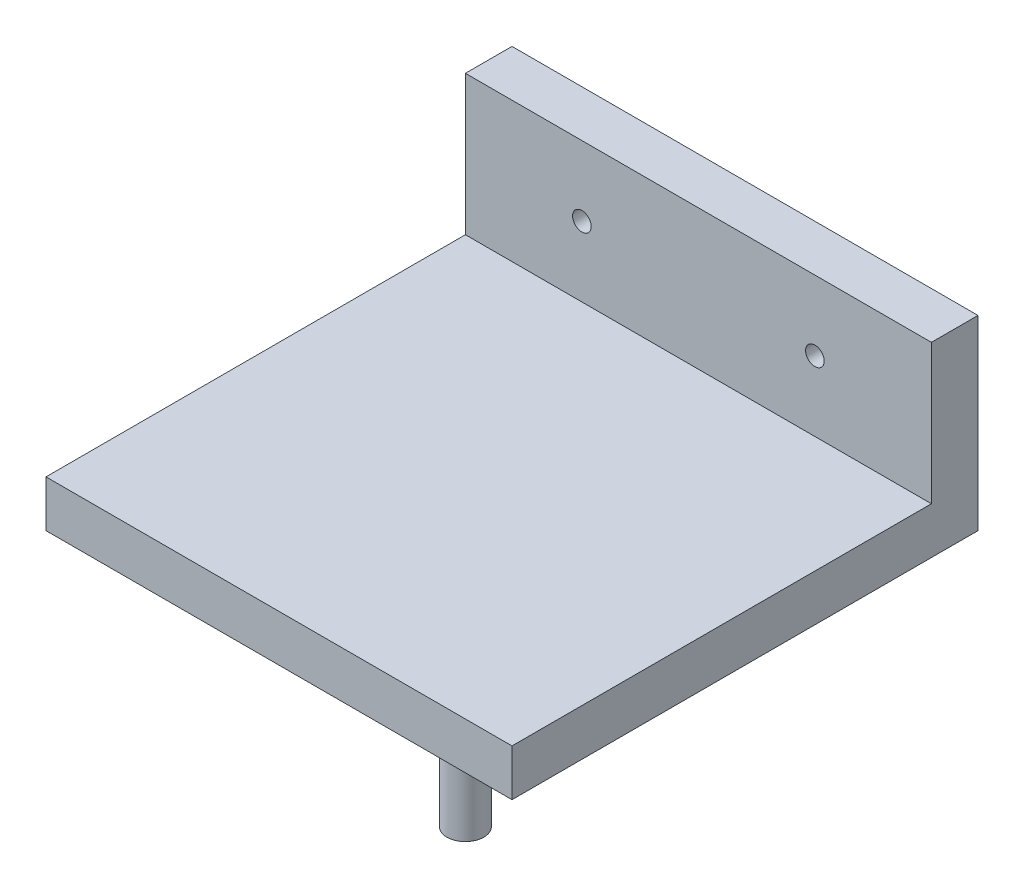
SolidWorks part; units mm, degrees
ref_plane "Front Plane" through (0, 0, 0) normal (0, 0, 1) x (1, 0, 0)
ref_plane "Top Plane" through (0, 0, 0) normal (0, 1, 0) x (1, 0, 0)
ref_plane "Right Plane" through (0, 0, 0) normal (1, 0, 0) x (0, 0, -1)
sketch "Sketch1" plane through (0, 0, 0) normal (0, 0, 1) x (1, 0, 0)
  line L1 (-50, 20) -> (50, 20)
  line L2 (-50, 20) -> (-50, -20)
  line L3 (-50, -20) -> (50, -20)
  line L4 (50, 20) -> (50, -20)
  line L5 (-50, 20) -> (50, -20) construction
  line L6 (-50, -20) -> (50, 20) construction
  point P0 (0, 0)
  dimension "D1" = 40
  dimension "D2" = 100
extrude "Boss-Extrude1" add sketch "Sketch1" along normal blind 10
sketch "Sketch2" plane through (0, 0, 10) normal (0, 0, 1) x (1, 0, 0)
  line L0 (50, -20) -> (50, 20) construction
  line L1 (-50, -20) -> (50, -20)
  line L2 (-50, -20) -> (-50, -10)
  line L3 (-50, -10) -> (50, -10)
  line L4 (50, -20) -> (50, -10)
  dimension "D1" = 10
extrude "Boss-Extrude2" add sketch "Sketch2" along normal blind 90
sketch "Sketch3" plane through (0, -20, 0) normal (0, -1, 0) x (1, 0, 0)
  line L0 (-50, 100) -> (0, 100) construction
  line L1 (-50, 100) -> (50, 100) construction
  line L2 (0, 100) -> (0, 60) construction
  circle A0 centre (0, 60) radius 3.95
  dimension "D2" = 7.9
  dimension "D1" = 40
extrude "Boss-Extrude3" add sketch "Sketch3" along normal blind 50
sketch "Sketch4" plane through (0, 0, 10) normal (0, 0, 1) x (1, 0, 0)
  line L0 (-50, 20) -> (-50, 5) construction
  line L1 (-50, 20) -> (-50, -10) construction
  line L2 (-50, 5) -> (0, 5) construction
  line L3 (0, 5) -> (0, 11.6546) construction
  circle A0 centre (-25, 5) radius 2
  circle A1 centre (25, 5) radius 2
  dimension "D1" = 4
extrude "Cut-Extrude1" cut sketch "Sketch4" against normal blind 50
